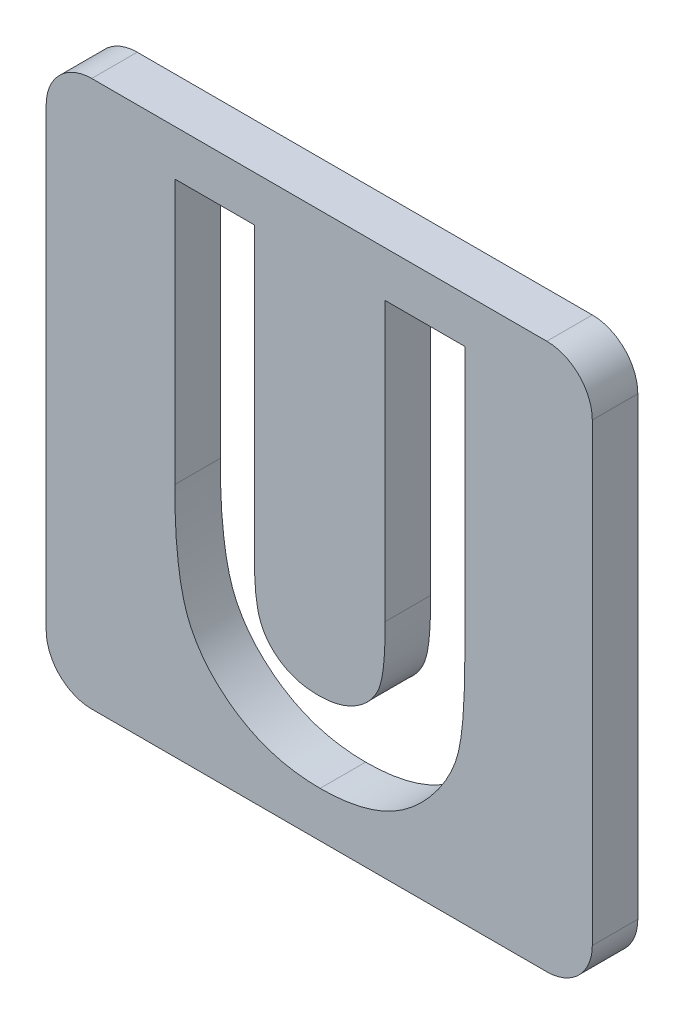
SolidWorks part; units mm, degrees
ref_plane "Front Plane" through (0, 0, 0) normal (0, 0, 1) x (1, 0, 0)
ref_plane "Top Plane" through (0, 0, 0) normal (0, 1, 0) x (1, 0, 0)
ref_plane "Right Plane" through (0, 0, 0) normal (1, 0, 0) x (0, 0, -1)
sketch "Sketch1" plane through (0, 0, 0) normal (0, 0, 1) x (1, 0, 0)
  line L1 (-50, 60) -> (50, 60)
  line L2 (-60, 50) -> (-60, -50)
  line L3 (-50, -60) -> (50, -60)
  line L4 (60, 50) -> (60, -50)
  line L5 (-60, 60) -> (60, -60) construction
  line L6 (-60, -60) -> (60, 60) construction
  arc A0 (-60, -50) -> (-50, -60) centre (-50, -50) ccw
  arc A1 (50, -60) -> (60, -50) centre (50, -50) ccw
  arc A2 (50, 60) -> (60, 50) centre (50, 50) cw
  arc A3 (-50, 60) -> (-60, 50) centre (-50, 50) ccw
  point P0 (0, 0)
  dimension "D3" = 10
  dimension "D1" = 120
  dimension "D2" = 120
extrude "Boss-Extrude1" add sketch "Sketch1" along normal blind 10 contours A3 L2 A0 L3 A1 L4 A2 L1
sketch "Sketch2" plane through (0, 0, 10) normal (0, 0, 1) x (1, 0, 0)
  line L0 (0, 0) -> (0, 40) construction
  line L1 (-50, 50) -> (50, 50) construction
  line L2 (-50, 50) -> (-50, -50) construction
  line L3 (-50, -50) -> (50, -50) construction
  line L4 (50, 50) -> (50, -50) construction
  line L5 (-50, 50) -> (50, -50) construction
  line L6 (-50, -50) -> (50, 50) construction
  line L7 (0, 40) -> (-40, 40) construction
  line L8 (-40, 40) -> (-40, 0) construction
  line L9 (-40, 0) -> (0, 0) construction
  line L11 (0, 20) -> (-20, 20) construction
  line L12 (-20, 40) -> (-20, 20) construction
  circle A0 centre (0, 40) radius 4 construction
  circle A1 centre (0, 20) radius 4 construction
  circle A2 centre (0, 0) radius 4 construction
  circle A3 centre (-20, 20) radius 4 construction
  circle A4 centre (-20, 40) radius 4 construction
  circle A5 centre (-40, 40) radius 4 construction
  circle A6 centre (0, 0) radius 4 construction
  circle A7 centre (20, 0) radius 4 construction
  circle A8 centre (40, 0) radius 4 construction
  circle A9 centre (40, 20) radius 4 construction
  circle A10 centre (40, 40) radius 4 construction
  circle A11 centre (20, 20) radius 4 construction
  circle A12 centre (0, 0) radius 4 construction
  circle A13 centre (0, -20) radius 4 construction
  circle A14 centre (0, -40) radius 4 construction
  circle A15 centre (20, -40) radius 4 construction
  circle A16 centre (40, -40) radius 4 construction
  circle A17 centre (20, -20) radius 4 construction
  circle A18 centre (0, 0) radius 4 construction
  circle A19 centre (-20, 0) radius 4 construction
  circle A20 centre (-40, 0) radius 4 construction
  circle A21 centre (-40, -20) radius 4 construction
  circle A22 centre (-40, -40) radius 4 construction
  circle A23 centre (-20, -20) radius 4 construction
  text T0 "U" font "Century Gothic" height 97.5
  point P0 (0, 0)
  point P55 (0, 0)
  dimension "D4" = 8
  dimension "D1" = 100
  dimension "D2" = 100
  dimension "D3" = 40
  dimension "D5" = 4
extrude "Cut-Extrude34" cut sketch "Sketch2" against normal blind 10
